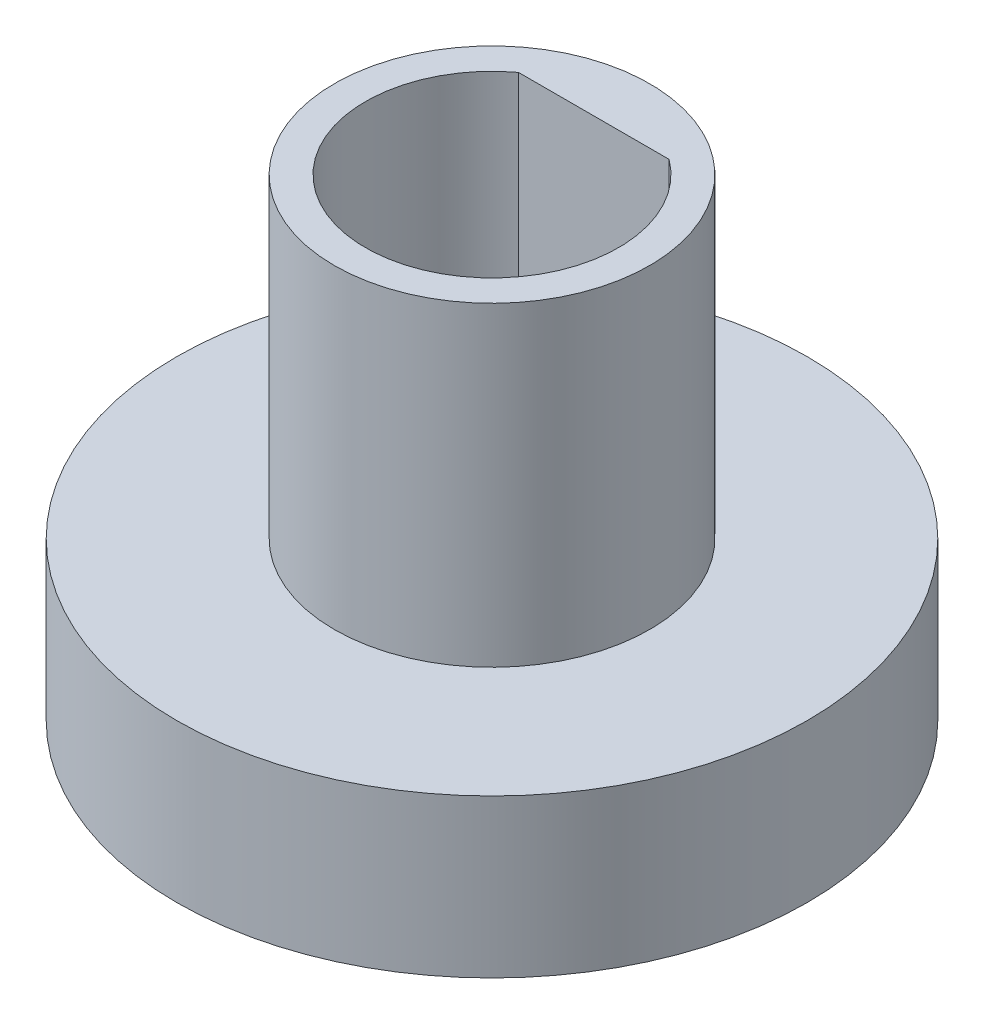
SolidWorks part; units mm, degrees
ref_plane "Front Plane" through (0, 0, 0) normal (0, 0, 1) x (1, 0, 0)
ref_plane "Top Plane" through (0, 0, 0) normal (0, 1, 0) x (1, 0, 0)
ref_plane "Right Plane" through (0, 0, 0) normal (1, 0, 0) x (0, 0, -1)
sketch "Sketch1" plane through (0, 0, 0) normal (0, 1, 0) x (1, 0, 0)
  circle A0 centre (0, 0) radius 6.35
  dimension "D1" = 12.7
extrude "Boss-Extrude1" add sketch "Sketch1" along normal blind 3.175
sketch "Sketch2" plane through (0, 3.175, 0) normal (0, 1, 0) x (1, 0, 0)
  circle A0 centre (0, 0) radius 3.175
  dimension "D1" = 6.35
extrude "Boss-Extrude2" add sketch "Sketch2" along normal blind 6.35
sketch "Sketch3" plane through (0, 9.525, 0) normal (0, 1, 0) x (1, 0, 0)
  line L0 (0, 0) -> (-2.55, 0) construction
  line L1 (-2.55, 0) -> (2.55, 0) construction
  line L2 (0, -2.55) -> (0, 2.05) construction
  line L3 (-1.5166, 2.05) -> (1.5166, 2.05)
  arc A0 (-1.5166, 2.05) -> (1.5166, 2.05) centre (0, 0) ccw
  dimension "D1" = 5.1
  dimension "D2" = 4.6
extrude "Cut-Extrude1" cut sketch "Sketch3" against normal through all
